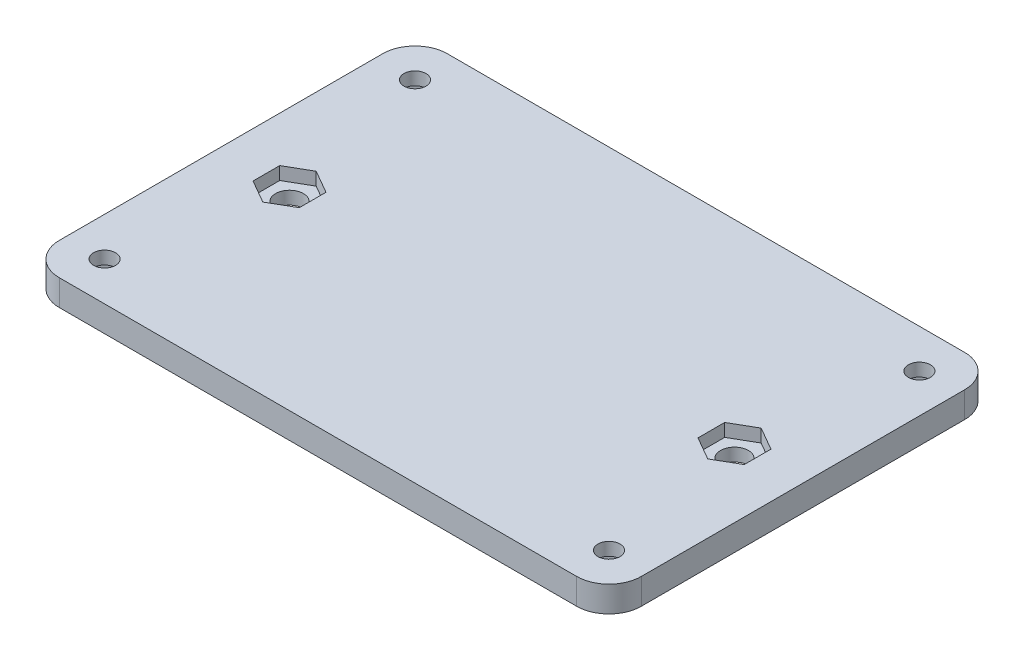
SolidWorks part; units mm, degrees
ref_plane "Front Plane" through (0, 0, 0) normal (0, 0, 1) x (1, 0, 0)
ref_plane "Top Plane" through (0, 0, 0) normal (0, 1, 0) x (1, 0, 0)
ref_plane "Right Plane" through (0, 0, 0) normal (1, 0, 0) x (0, 0, -1)
sketch "Sketch1" plane through (0, 0, 0) normal (0, 1, 0) x (1, 0, 0)
  line L1 (-45, 30) -> (45, 30)
  line L2 (-45, 30) -> (-45, -30)
  line L3 (-45, -30) -> (45, -30)
  line L4 (45, 30) -> (45, -30)
  dimension "D1" = 90
  dimension "D2" = 60
  dimension "D3" = 45
  dimension "D4" = 30
extrude "Boss-Extrude1" add sketch "Sketch1" along normal blind 4
sketch "Sketch2" plane through (0, 4, 0) normal (0, 1, 0) x (1, 0, 0)
  line L0 (45, 30) -> (-45, 30) construction
  line L1 (-45, 30) -> (-45, -30) construction
  line L2 (-45, -30) -> (45, -30) construction
  line L3 (45, -30) -> (45, 30) construction
  circle A0 centre (-34.4, -0.0026) radius 2.15
  circle A1 centre (34.4, 0.0004) radius 2.15
  circle A2 centre (-39, 24) radius 1.7
  circle A3 centre (-39, -24) radius 1.7
  circle A4 centre (39, -24) radius 1.7
  circle A5 centre (39, 24) radius 1.7
  point P21 (0, 0)
  dimension "D2" = 4.3
  dimension "D6" = 3.4
  dimension "D1" = 68.8
  dimension "D3" = 34.4
  dimension "D4" = 30.0026
  dimension "D5" = 29.9996
  dimension "D7" = 6
  dimension "D8" = 6
  dimension "D9" = 6
  dimension "D10" = 6
  dimension "D11" = 6
  dimension "D12" = 6
  dimension "D13" = 6
  dimension "D14" = 6
extrude "Cut-Extrude1" cut sketch "Sketch2" against normal blind 4
sketch "Sketch3" plane through (0, 4, 0) normal (0, 1, 0) x (1, 0, 0)
  line L0 (-45, 30) -> (-45, -30) construction
  line L1 (-30.825, 2.0614) -> (-34.4, 4.1254)
  line L2 (-34.4, 4.1254) -> (-37.975, 2.0614)
  line L3 (-37.975, 2.0614) -> (-37.975, -2.0667)
  line L4 (-37.975, -2.0667) -> (-34.4, -4.1307)
  line L5 (-34.4, -4.1307) -> (-30.825, -2.0667)
  line L6 (-30.825, -2.0667) -> (-30.825, 2.0614)
  line L7 (37.975, 2.0644) -> (34.4, 4.1284)
  line L8 (34.4, 4.1284) -> (30.825, 2.0644)
  line L9 (30.825, 2.0644) -> (30.825, -2.0636)
  line L10 (30.825, -2.0636) -> (34.4, -4.1277)
  line L11 (34.4, -4.1277) -> (37.975, -2.0636)
  line L12 (37.975, -2.0636) -> (37.975, 2.0644)
  line L13 (45, -30) -> (45, 30) construction
  circle A0 centre (-34.4, -0.0026) radius 3.575 construction
  circle A1 centre (34.4, 0.0004) radius 3.575 construction
  dimension "D1" = 7.15
  dimension "D2" = 7.15
extrude "Cut-Extrude2" cut sketch "Sketch3" against normal blind 2
sketch "Sketch4" plane through (0, 0, 0) normal (0, -1, 0) x (1, 0, 0)
  line L0 (-45, -30) -> (-45, 30) construction
  line L1 (-36.2, 25.6166) -> (-39, 27.2332)
  line L2 (-39, 27.2332) -> (-41.8, 25.6166)
  line L3 (-41.8, 25.6166) -> (-41.8, 22.3834)
  line L4 (-41.8, 22.3834) -> (-39, 20.7668)
  line L5 (-39, 20.7668) -> (-36.2, 22.3834)
  line L6 (-36.2, 22.3834) -> (-36.2, 25.6166)
  line L7 (-36.2, -22.3834) -> (-39, -20.7668)
  line L8 (-39, -20.7668) -> (-41.8, -22.3834)
  line L9 (-41.8, -22.3834) -> (-41.8, -25.6166)
  line L10 (-41.8, -25.6166) -> (-39, -27.2332)
  line L11 (-39, -27.2332) -> (-36.2, -25.6166)
  line L12 (-36.2, -25.6166) -> (-36.2, -22.3834)
  line L13 (41.8, -22.3834) -> (39, -20.7668)
  line L14 (39, -20.7668) -> (36.2, -22.3834)
  line L15 (36.2, -22.3834) -> (36.2, -25.6166)
  line L16 (36.2, -25.6166) -> (39, -27.2332)
  line L17 (39, -27.2332) -> (41.8, -25.6166)
  line L18 (41.8, -25.6166) -> (41.8, -22.3834)
  line L19 (41.8, 25.6166) -> (39, 27.2332)
  line L20 (39, 27.2332) -> (36.2, 25.6166)
  line L21 (36.2, 25.6166) -> (36.2, 22.3834)
  line L22 (36.2, 22.3834) -> (39, 20.7668)
  line L23 (39, 20.7668) -> (41.8, 22.3834)
  line L24 (41.8, 22.3834) -> (41.8, 25.6166)
  line L25 (45, 30) -> (45, -30) construction
  circle A0 centre (-39, 24) radius 2.8 construction
  circle A1 centre (-39, -24) radius 2.8 construction
  circle A2 centre (39, -24) radius 2.8 construction
  circle A3 centre (39, 24) radius 2.8 construction
  dimension "D1" = 5.6
  dimension "D2" = 5.6
  dimension "D3" = 5.6
  dimension "D4" = 5.6
extrude "Cut-Extrude3" cut sketch "Sketch4" against normal blind 2
fillet "Fillet3" radius 5 4 edges at (-45, 2, 30) (-45, 2, -30) (45, 2, 30) (45, 2, -30)
